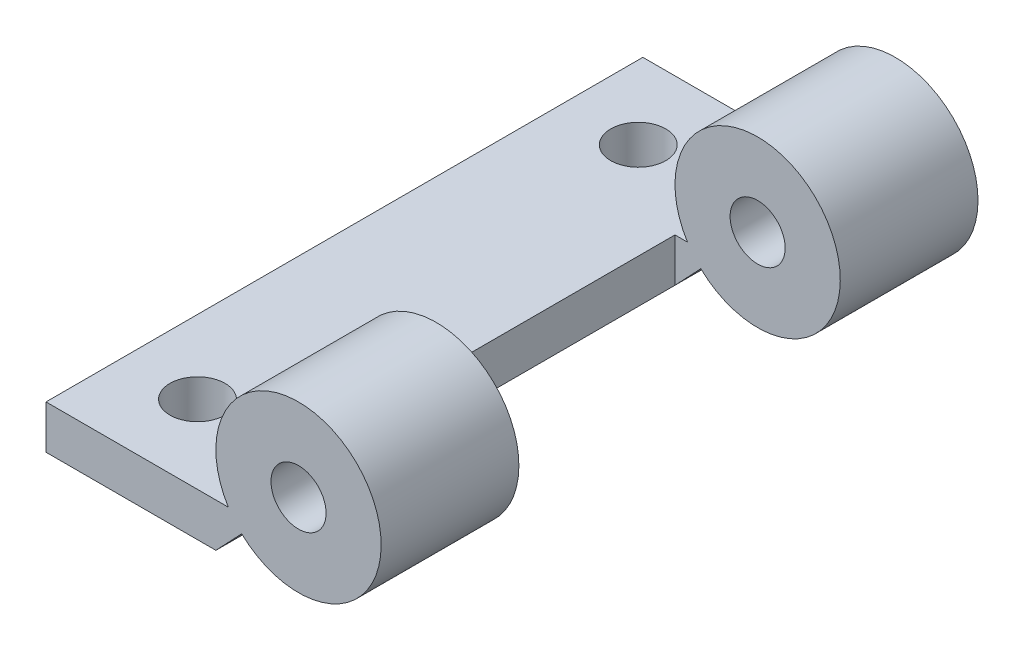
SolidWorks part; units mm, degrees
ref_plane "前视基准面" through (0, 0, 0) normal (0, 0, 1) x (1, 0, 0)
ref_plane "上视基准面" through (0, 0, 0) normal (0, 1, 0) x (1, 0, 0)
ref_plane "右视基准面" through (0, 0, 0) normal (1, 0, 0) x (0, 0, -1)
sketch "草图1" plane through (0, 0, 0) normal (0, 0, 1) x (1, 0, 0)
  line L2 (-27.5, 4.75) -> (-27.5, 0)
  line L3 (-27.5, 0) -> (-9, 0)
  line L4 (-9, 0) -> (-6.1897, 2.9664)
  line L5 (-7.6444, 4.75) -> (-27.5, 4.75)
  arc A0 (-6.1897, 2.9664) -> (-7.6444, 4.75) centre (0, 9.5) ccw
extrude "凸台-拉伸1" add sketch "草图1" along normal blind 65
sketch "草图2" plane through (0, 4.75, 0) normal (0, 1, 0) x (1, 0, 0)
  line L0 (-27.5, 0) -> (-19.5, 0)
  line L1 (-7.6444, 0) -> (-27.5, 0) construction
  circle A0 centre (-19.5, -8.5) radius 3
  circle A1 centre (-19.5, -56.5) radius 3
extrude "切除-拉伸1" cut sketch "草图2" against normal blind 65 contours A0 | A1
sketch "草图3" plane through (0, 4.75, 0) normal (0, 1, 0) x (1, 0, 0)
  line L1 (-9, 0) -> (-9, -65) construction
  line L3 (-9, -15) -> (-9, -50)
  line L4 (-9, -15) -> (10.3331, -15)
  line L5 (-9, -50) -> (10.3331, -50)
  line L6 (10.3331, -15) -> (10.3331, -50)
extrude "切除-拉伸2" cut sketch "草图3" against normal mid plane 65
sketch "草图4" plane through (0, 0, 65) normal (0, 0, 1) x (1, 0, 0)
  circle A0 centre (0, 9.5) radius 3
extrude "切除-拉伸3" cut sketch "草图4" against normal blind 65
